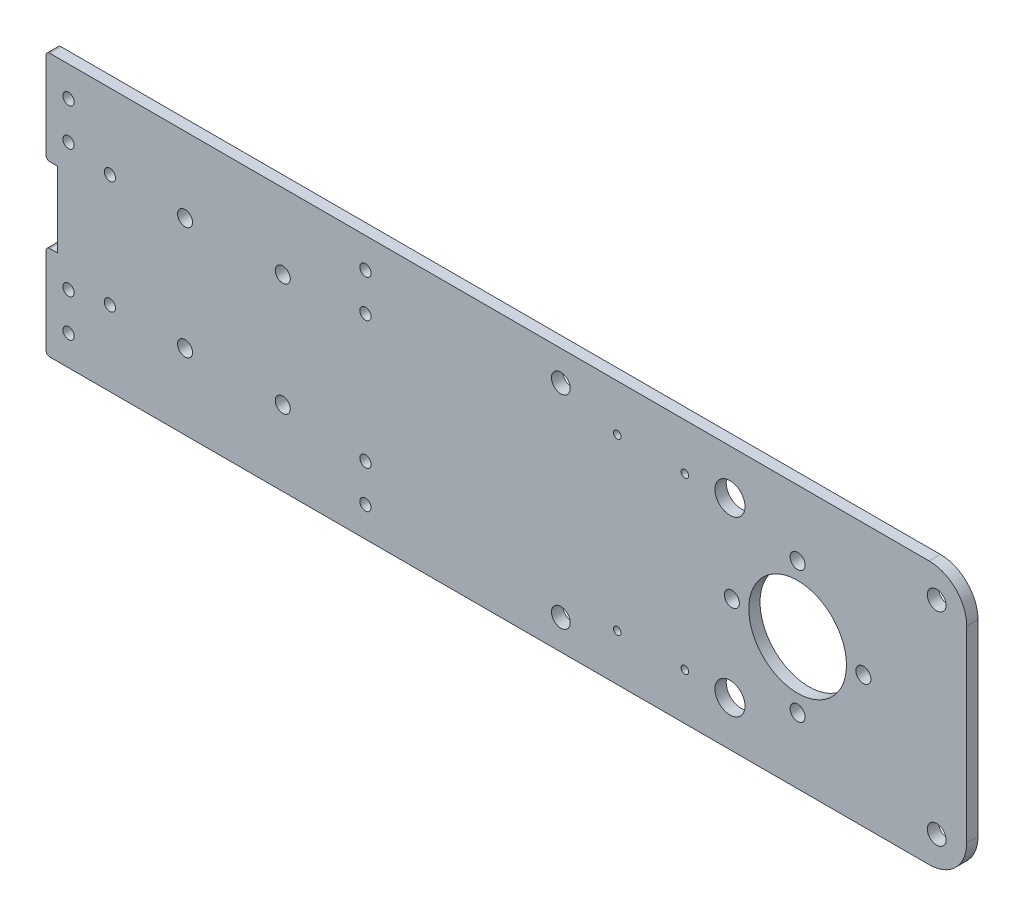
SolidWorks part; units mm, degrees
material "A-玻璃纤维"
ref_plane "前视基准面" through (0, 0, 0) normal (0, 0, 1) x (1, 0, 0)
ref_plane "上视基准面" through (0, 0, 0) normal (0, 1, 0) x (1, 0, 0)
ref_plane "右视基准面" through (0, 0, 0) normal (1, 0, 0) x (0, 0, -1)
sketch "草图1" plane through (0, 0, 0) normal (0, 0, 1) x (1, 0, 0)
  line L1 (-122.5, -35) -> (122.5, -35)
  line L2 (-122.5, -35) -> (-122.5, 35)
  line L3 (-122.5, 35) -> (122.5, 35)
  line L4 (122.5, -35) -> (122.5, 35)
  line L5 (-122.5, -35) -> (122.5, 35) construction
  line L6 (-122.5, 35) -> (122.5, -35) construction
  point P0 (0, 0)
  dimension "D1" = 70
  dimension "D2" = 245
extrude "凸台-拉伸1" add sketch "草图1" along normal blind 3
sketch "草图3" plane through (0, 0, 3) normal (0, 0, 1) x (1, 0, 0)
  line L0 (-122.5, 0) -> (122.5, 0) construction
  line L1 (-122.5, 35) -> (-122.5, -35) construction
  line L2 (122.5, -35) -> (122.5, 35) construction
  line L3 (-72.5, 35) -> (-72.5, -35) construction
  line L4 (122.5, 35) -> (-122.5, 35) construction
  line L5 (-122.5, -35) -> (122.5, -35) construction
  circle A0 centre (-85.5, 15) radius 2
  circle A1 centre (-59.5, 15) radius 2
  circle A2 centre (-59.5, -15) radius 2
  circle A3 centre (-85.5, -15) radius 2
  dimension "D4" = 4
  dimension "D1" = 50
  dimension "D2" = 15
  dimension "D3" = 13
extrude "切除-拉伸2" cut sketch "草图3" against normal through all
sketch "草图5" plane through (0, 0, 3) normal (0, 0, 1) x (1, 0, 0)
  line L0 (-122.5, 0) -> (122.5, 0) construction
  line L1 (-122.5, 35) -> (-122.5, -35) construction
  line L2 (122.5, -35) -> (122.5, 35) construction
  line L4 (-122.5, -10) -> (-119.5, -10)
  line L5 (-122.5, -10) -> (-122.5, 10)
  line L6 (-122.5, 10) -> (-119.5, 10)
  line L7 (-119.5, -10) -> (-119.5, 10)
  line L8 (-122.5, -10) -> (-119.5, 10) construction
  line L9 (-122.5, 10) -> (-119.5, -10) construction
  point P6 (-121, 0)
  dimension "D1" = 3
  dimension "D2" = 20
extrude "切除-拉伸4" cut sketch "草图5" against normal through all
fillet "圆角1" radius 1 4 edges at (-122.5, 35, 1.5) (-122.5, -35, 1.5) (-122.5, -10, 1.5) (-122.5, 10, 1.5)
sketch "草图6" plane through (0, 0, 3) normal (0, 0, 1) x (1, 0, 0)
  line L0 (-119.5, 0) -> (122.5, 0) construction
  line L1 (-119.5, -10) -> (-119.5, 10) construction
  line L2 (122.5, -35) -> (122.5, 35) construction
  line L3 (-122.5, 34) -> (-122.5, 11) construction
  line L4 (122.5, 35) -> (-121.5, 35) construction
  circle A0 centre (-116.5, 27) radius 1.5
  circle A1 centre (-116.5, 17) radius 1.5
  circle A2 centre (-116.5, -17) radius 1.5
  circle A3 centre (-116.5, -27) radius 1.5
  dimension "D3" = 3
  dimension "D1" = 6
  dimension "D2" = 8
  dimension "D4" = 10
extrude "切除-拉伸5" cut sketch "草图6" against normal through all
sketch "草图7" plane through (0, 0, 3) normal (0, 0, 1) x (1, 0, 0)
  line L0 (-119.5, 0) -> (122.5, 0) construction
  line L1 (-119.5, -10) -> (-119.5, 10) construction
  line L2 (122.5, -35) -> (122.5, 35) construction
  line L3 (-122.5, 34) -> (-122.5, 11) construction
  circle A0 centre (-105.5, 15) radius 1.5
  circle A1 centre (-105.5, -15) radius 1.5
  dimension "D3" = 3
  dimension "D1" = 15
  dimension "D2" = 17
extrude "切除-拉伸6" cut sketch "草图7" against normal through all
sketch "草图8" plane through (0, 0, 3) normal (0, 0, 1) x (1, 0, 0)
  line L0 (-119.5, 0) -> (122.5, 0) construction
  line L1 (-119.5, -10) -> (-119.5, 10) construction
  line L2 (122.5, -35) -> (122.5, 35) construction
  line L3 (122.5, 35) -> (-121.5, 35) construction
  line L4 (-122.5, 34) -> (-122.5, 11) construction
  circle A0 centre (-37.5, 27) radius 1.5
  circle A1 centre (-37.5, 17) radius 1.5
  circle A2 centre (-37.5, -17) radius 1.5
  circle A3 centre (-37.5, -27) radius 1.5
  dimension "D3" = 3
  dimension "D1" = 8
  dimension "D2" = 85
  dimension "D4" = 10
extrude "切除-拉伸7" cut sketch "草图8" against normal through all
sketch "草图9" plane through (0, 0, 3) normal (0, 0, 1) x (1, 0, 0)
  line L0 (-119.5, 0) -> (122.5, 0) construction
  line L1 (-119.5, -10) -> (-119.5, 10) construction
  line L2 (122.5, -35) -> (122.5, 35) construction
  circle A0 centre (77.5, 0) radius 13
  dimension "D1" = 26
  dimension "D2" = 197
extrude "切除-拉伸8" cut sketch "草图9" against normal through all
sketch "草图10" plane through (0, 0, 3) normal (0, 0, 1) x (1, 0, 0)
  line L0 (64.5, 0) -> (90.5, 0) construction
  line L1 (77.5, -13) -> (77.5, 13) construction
  circle A0 centre (77.5, 0) radius 13 construction
  circle A1 centre (77.5, 17.5) radius 2
  circle A2 centre (60, 0) radius 2
  circle A3 centre (95, 0) radius 2
  circle A4 centre (77.5, -17.5) radius 2
  dimension "D3" = 4
  dimension "D1" = 17.5
  dimension "D2" = 17.5
extrude "切除-拉伸9" cut sketch "草图10" against normal through all
fillet "圆角2" radius 10 2 edges at (122.5, -35, 1.5) (122.5, 35, 1.5)
sketch "草图11" plane through (0, 0, 0) normal (0, 0, -1) x (-1, 0, 0)
  line L0 (-122.5, 0) -> (119.5, 0) construction
  line L1 (-122.5, -25) -> (-122.5, 25) construction
  line L2 (119.5, -10) -> (119.5, 10) construction
  circle A0 centre (-114.5, 27) radius 2.5
  circle A1 centre (-14.5, 27) radius 2.5
  circle A2 centre (-14.5, -27) radius 2.5
  circle A3 centre (-114.5, -27) radius 2.5
  dimension "D1" = 5
  dimension "D2" = 5
  dimension "D3" = 27
  dimension "D4" = 8
  dimension "D5" = 100
extrude "切除-拉伸10" cut sketch "草图11" against normal through all
sketch "草图12" plane through (0, 0, 0) normal (0, 0, -1) x (-1, 0, 0)
  line L0 (-122.5, 0) -> (119.5, 0) construction
  line L1 (-122.5, -25) -> (-122.5, 25) construction
  line L2 (119.5, -10) -> (119.5, 10) construction
  circle A0 centre (-59.5, 23) radius 4
  circle A1 centre (-77.5, 0) radius 13 construction
  circle A2 centre (-59.5, -23) radius 4
  dimension "D2" = 8
  dimension "D1" = 18
  dimension "D3" = 23
extrude "切除-拉伸11" cut sketch "草图12" against normal through all both and the other way through all
sketch "草图13" plane through (0, 0, 0) normal (0, 0, -1) x (-1, 0, 0)
  line L0 (-122.5, 0) -> (119.5, 0) construction
  line L1 (-122.5, -25) -> (-122.5, 25) construction
  line L2 (119.5, -10) -> (119.5, 10) construction
  circle A0 centre (-47.5, 22.6) radius 1
  circle A1 centre (-29.5, 22.6) radius 1
  circle A2 centre (-29.5, -22.6) radius 1
  circle A3 centre (-47.5, -22.6) radius 1
  dimension "D2" = 2
  dimension "D1" = 22.6
  dimension "D3" = 18
  dimension "D4" = 75
extrude "切除-拉伸12" cut sketch "草图13" against normal through all
